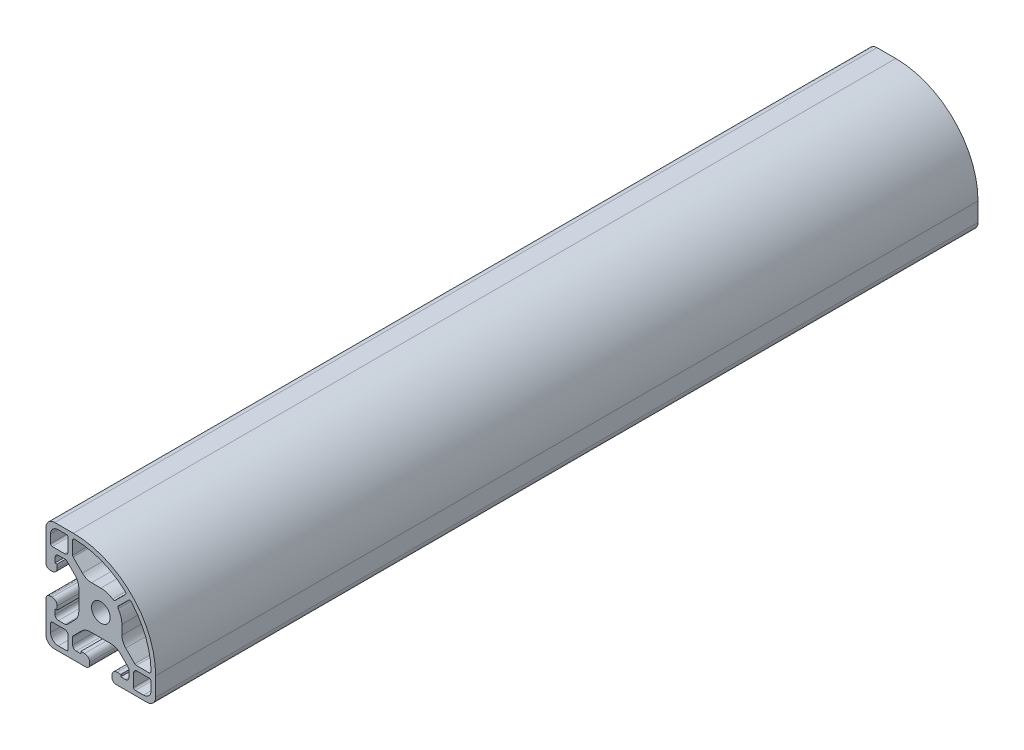
SolidWorks part; units mm, degrees
material "6105-T5 Aluminum"
ref_plane "Front Plane" through (0, 0, 0) normal (0, 0, 1) x (1, 0, 0)
ref_plane "Top Plane" through (0, 0, 0) normal (0, 1, 0) x (1, 0, 0)
ref_plane "Right Plane" through (0, 0, 0) normal (1, 0, 0) x (0, 0, -1)
sketch "Sketch1" plane through (0, 0, 0) normal (0, 0, 1) x (1, 0, 0)
  line L0 (-13.5527, -20) -> (-17.1424, -20)
  line L1 (-5.5403, -20) -> (-13.5527, -20)
  line L2 (-4.06, -17.8048) -> (-4.06, -18.5197)
  line L3 (-7.2807, -15.94) -> (-5.9248, -15.94)
  line L4 (-7.2807, -16.7) -> (-7.2807, -15.94)
  line L5 (-9.015, -16.7) -> (-7.2807, -16.7)
  line L6 (-10.285, -13.0538) -> (-10.285, -15.43)
  line L7 (-7.0978, -9.4312) -> (-9.9772, -12.3106)
  line L8 (3.739, -8.04) -> (-3.739, -8.04)
  line L9 (10.0243, -12.3578) -> (7.0978, -9.4312)
  line L10 (10.285, -15.3633) -> (10.285, -12.9871)
  line L11 (7.2807, -16.7) -> (8.9483, -16.7)
  line L12 (7.2807, -15.94) -> (7.2807, -16.7)
  line L13 (5.9248, -15.94) -> (7.2807, -15.94)
  line L14 (4.06, -18.5197) -> (4.06, -17.8048)
  line L15 (12.5637, -20) -> (5.5403, -20)
  line L16 (16.833, -20) -> (12.5637, -20)
  line L17 (20, -10) -> (20, -16.833)
  line L18 (-11.925, -17.705) -> (-11.925, -13.195)
  line L19 (-15.535, -18.335) -> (-12.555, -18.335)
  line L20 (7.6793, 0) -> (7.6793, -3.3783)
  line L21 (9.0705, -6.7371) -> (12.4008, -10.0673)
  line L22 (12.9382, -10.2899) -> (17.5861, -10.2899)
  line L23 (10.0603, 8.8935) -> (6.4446, 5.2779)
  line L24 (17.7201, -11.9399) -> (13.2101, -11.9399)
  line L25 (18.3501, -15.5499) -> (18.3501, -12.5699)
  line L26 (12.5701, -18.3499) -> (15.5501, -18.3499)
  line L27 (11.9401, -13.2099) -> (11.9401, -17.7199)
  line L28 (-22.9183, 0) -> (-20.5421, 0) construction
  line L29 (-19.163, -19.163) -> (19.163, 19.163) construction
  line L30 (-13.2099, 11.9401) -> (-17.7199, 11.9401)
  line L31 (-18.3499, 12.5701) -> (-18.3499, 15.5501)
  line L32 (-15.5499, 18.3501) -> (-12.5699, 18.3501)
  line L33 (-11.9399, 17.7201) -> (-11.9399, 13.2101)
  line L34 (8.8935, 10.0603) -> (5.2779, 6.4446)
  line L35 (-10.2899, 12.9382) -> (-10.2899, 17.5861)
  line L36 (-6.7371, 9.0705) -> (-10.0673, 12.4008)
  line L37 (0, 7.6793) -> (-3.3783, 7.6793)
  line L38 (-18.335, -15.535) -> (-18.335, -12.555)
  line L39 (-17.705, -11.925) -> (-13.195, -11.925)
  line L40 (-10, 20) -> (-16.833, 20)
  line L41 (-20, 16.833) -> (-20, 12.5637)
  line L42 (-20, 12.5637) -> (-20, 5.5403)
  line L43 (-18.5197, 4.06) -> (-17.8048, 4.06)
  line L44 (-15.94, 5.9248) -> (-15.94, 7.2807)
  line L45 (-15.94, 7.2807) -> (-16.7, 7.2807)
  line L46 (-16.7, 7.2807) -> (-16.7, 8.9483)
  line L47 (-15.3633, 10.285) -> (-12.9871, 10.285)
  line L48 (-12.3578, 10.0243) -> (-9.4312, 7.0978)
  line L49 (-8.04, 3.739) -> (-8.04, -3.739)
  line L50 (-9.4312, -7.0978) -> (-12.3106, -9.9772)
  line L51 (-13.0538, -10.285) -> (-15.43, -10.285)
  line L52 (-16.7, -9.015) -> (-16.7, -7.2807)
  line L53 (-16.7, -7.2807) -> (-15.94, -7.2807)
  line L54 (-15.94, -7.2807) -> (-15.94, -5.9248)
  line L55 (-17.8048, -4.06) -> (-18.5197, -4.06)
  line L56 (-20, -5.5403) -> (-20, -13.5527)
  line L57 (-20, -13.5527) -> (-20, -17.1424)
  line L58 (0, 0) -> (12.4293, 0) construction
  line L59 (0, 26.4613) -> (0, -24.589) construction
  arc A0 (-11.925, -17.705) -> (-12.555, -18.335) centre (-12.555, -17.705) cw
  arc A1 (-17.1424, -20) -> (-19.163, -19.163) centre (-17.1424, -17.1424) cw
  arc A2 (-4.06, -18.5197) -> (-5.5403, -20) centre (-5.5403, -18.5197) cw
  arc A3 (-5.9248, -15.94) -> (-4.06, -17.8048) centre (-5.9248, -17.8048) cw
  arc A4 (-9.015, -16.7) -> (-10.285, -15.43) centre (-9.015, -15.43) cw
  arc A5 (-10.285, -13.0538) -> (-9.9772, -12.3106) centre (-9.234, -13.0538) cw
  arc A6 (-7.0978, -9.4312) -> (-3.739, -8.04) centre (-3.739, -12.79) cw
  arc A7 (3.739, -8.04) -> (7.0978, -9.4312) centre (3.739, -12.79) cw
  arc A8 (10.0243, -12.3578) -> (10.285, -12.9871) centre (9.395, -12.9871) cw
  arc A9 (10.285, -15.3633) -> (8.9483, -16.7) centre (8.9483, -15.3633) cw
  arc A10 (4.06, -17.8048) -> (5.9248, -15.94) centre (5.9248, -17.8048) cw
  arc A11 (5.5403, -20) -> (4.06, -18.5197) centre (5.5403, -18.5197) cw
  arc A12 (20, -16.833) -> (16.833, -20) centre (16.833, -16.833) cw
  arc A13 (9.0705, -6.7371) -> (7.6793, -3.3783) centre (12.4293, -3.3783) cw
  arc A14 (12.9382, -10.2899) -> (12.4008, -10.0673) centre (12.9382, -9.5299) cw
  arc A15 (18.346, -9.517) -> (17.5861, -10.2899) centre (17.5861, -9.5299) cw
  arc A16 (11.1651, 8.8618) -> (18.346, -9.517) centre (-10, -10) cw
  arc A17 (10.0603, 8.8935) -> (11.1651, 8.8618) centre (10.5977, 8.3561) cw
  arc A18 (6.3533, 4.3136) -> (6.4446, 5.2779) centre (6.982, 4.7405) cw
  arc A19 (6.3533, 4.3136) -> (7.6793, 0) centre (0, 0) cw
  arc A20 (11.9401, -13.2099) -> (13.2101, -11.9399) centre (13.2101, -13.2099) cw
  arc A21 (17.7201, -11.9399) -> (18.3501, -12.5699) centre (17.7201, -12.5699) cw
  arc A22 (18.3501, -15.5499) -> (15.5501, -18.3499) centre (15.5501, -15.5499) cw
  arc A23 (12.5701, -18.3499) -> (11.9401, -17.7199) centre (12.5701, -17.7199) cw
  arc A28 (-18.3499, 12.5701) -> (-17.7199, 11.9401) centre (-17.7199, 12.5701) ccw
  arc A29 (-15.5499, 18.3501) -> (-18.3499, 15.5501) centre (-15.5499, 15.5501) ccw
  arc A30 (-11.9399, 17.7201) -> (-12.5699, 18.3501) centre (-12.5699, 17.7201) ccw
  arc A31 (-13.2099, 11.9401) -> (-11.9399, 13.2101) centre (-13.2099, 13.2101) ccw
  arc A32 (4.3136, 6.3533) -> (0, 7.6793) centre (0, 0) ccw
  arc A33 (4.3136, 6.3533) -> (5.2779, 6.4446) centre (4.7405, 6.982) ccw
  arc A34 (8.8935, 10.0603) -> (8.8618, 11.1651) centre (8.3561, 10.5977) ccw
  arc A35 (8.8618, 11.1651) -> (-9.517, 18.346) centre (-10, -10) ccw
  arc A36 (-9.517, 18.346) -> (-10.2899, 17.5861) centre (-9.5299, 17.5861) ccw
  arc A37 (-10.2899, 12.9382) -> (-10.0673, 12.4008) centre (-9.5299, 12.9382) ccw
  arc A38 (-6.7371, 9.0705) -> (-3.3783, 7.6793) centre (-3.3783, 12.4293) ccw
  circle A39 centre (0, 0) radius 3.4
  arc A40 (20, -10) -> (-10, 20) centre (-10, -10) ccw
  arc A41 (-16.833, 20) -> (-20, 16.833) centre (-16.833, 16.833) ccw
  arc A42 (-20, 5.5403) -> (-18.5197, 4.06) centre (-18.5197, 5.5403) ccw
  arc A43 (-17.8048, 4.06) -> (-15.94, 5.9248) centre (-17.8048, 5.9248) ccw
  arc A44 (-15.3633, 10.285) -> (-16.7, 8.9483) centre (-15.3633, 8.9483) ccw
  arc A45 (-12.3578, 10.0243) -> (-12.9871, 10.285) centre (-12.9871, 9.395) ccw
  arc A46 (-8.04, 3.739) -> (-9.4312, 7.0978) centre (-12.79, 3.739) ccw
  arc A47 (-9.4312, -7.0978) -> (-8.04, -3.739) centre (-12.79, -3.739) ccw
  arc A48 (-13.0538, -10.285) -> (-12.3106, -9.9772) centre (-13.0538, -9.234) ccw
  arc A49 (-16.7, -9.015) -> (-15.43, -10.285) centre (-15.43, -9.015) ccw
  arc A50 (-15.94, -5.9248) -> (-17.8048, -4.06) centre (-17.8048, -5.9248) ccw
  arc A51 (-18.5197, -4.06) -> (-20, -5.5403) centre (-18.5197, -5.5403) ccw
  arc A52 (-20, -17.1424) -> (-19.163, -19.163) centre (-17.1424, -17.1424) ccw
  arc A53 (-18.335, -15.535) -> (-15.535, -18.335) centre (-15.535, -15.535) ccw
  arc A54 (-17.705, -11.925) -> (-18.335, -12.555) centre (-17.705, -12.555) ccw
  arc A55 (-11.925, -13.195) -> (-13.195, -11.925) centre (-13.195, -13.195) ccw
  dimension "D2" = 6.8
  dimension "D7" = 30
  dimension "D1" = 40
  dimension "D3" = 20.57
  dimension "D4" = 3.3
  dimension "D5" = 4.06
  dimension "D6" = 8.12
  dimension "D8" = 20
  dimension "D9" = 7.9
extrude "Extrude1" add sketch "Sketch1" against normal blind 300
